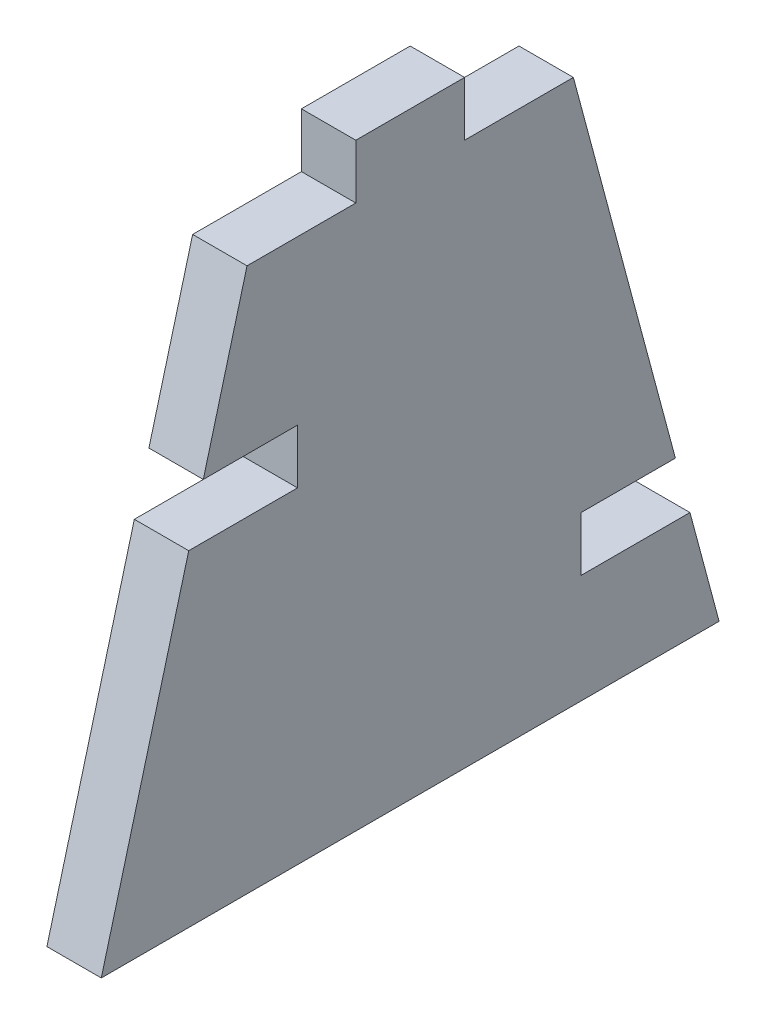
SolidWorks part; units mm, degrees
ref_plane "Front Plane" through (0, 0, 0) normal (0, 0, 1) x (1, 0, 0)
ref_plane "Top Plane" through (0, 0, 0) normal (0, 1, 0) x (1, 0, 0)
ref_plane "Right Plane" through (0, 0, 0) normal (1, 0, 0) x (0, 0, -1)
sketch "Sketch1" plane through (0, 0, 0) normal (1, 0, 0) x (0, 0, -1)
  line L0 (56.7949, 0) -> (-56.7949, 0)
  line L1 (-56.7949, 0) -> (-40.718, 60)
  line L2 (-30, 100) -> (-10, 100)
  line L3 (-10, 100) -> (-10, 110)
  line L4 (-10, 110) -> (10, 110)
  line L5 (0, 0) -> (0, 165.4832) construction
  line L6 (10, 100) -> (10, 110)
  line L7 (30, 100) -> (10, 100)
  line L8 (56.7949, 0) -> (51.4359, 20)
  line L9 (-38.0385, 70) -> (-20.718, 70)
  line L10 (-20.718, 70) -> (-20.718, 60)
  line L11 (-20.718, 60) -> (-40.718, 60)
  line L12 (48.7564, 30) -> (31.4359, 30)
  line L13 (31.4359, 30) -> (31.4359, 20)
  line L14 (31.4359, 20) -> (51.4359, 20)
  line L15 (-38.0385, 70) -> (-30, 100)
  line L16 (48.7564, 30) -> (30, 100)
  point P9 (0, 110)
  dimension "D1" = 30
  dimension "sketch1" = 100
  dimension "D2" = 10
  dimension "D3" = 10
  dimension "D4" = 75
  dimension "D5" = 60
  dimension "D6" = 20
  dimension "D7" = 10
  dimension "D8" = 20
  dimension "D9" = 20
  dimension "D10" = 10
extrude "Boss-Extrude1" add sketch "Sketch1" along normal blind 10
